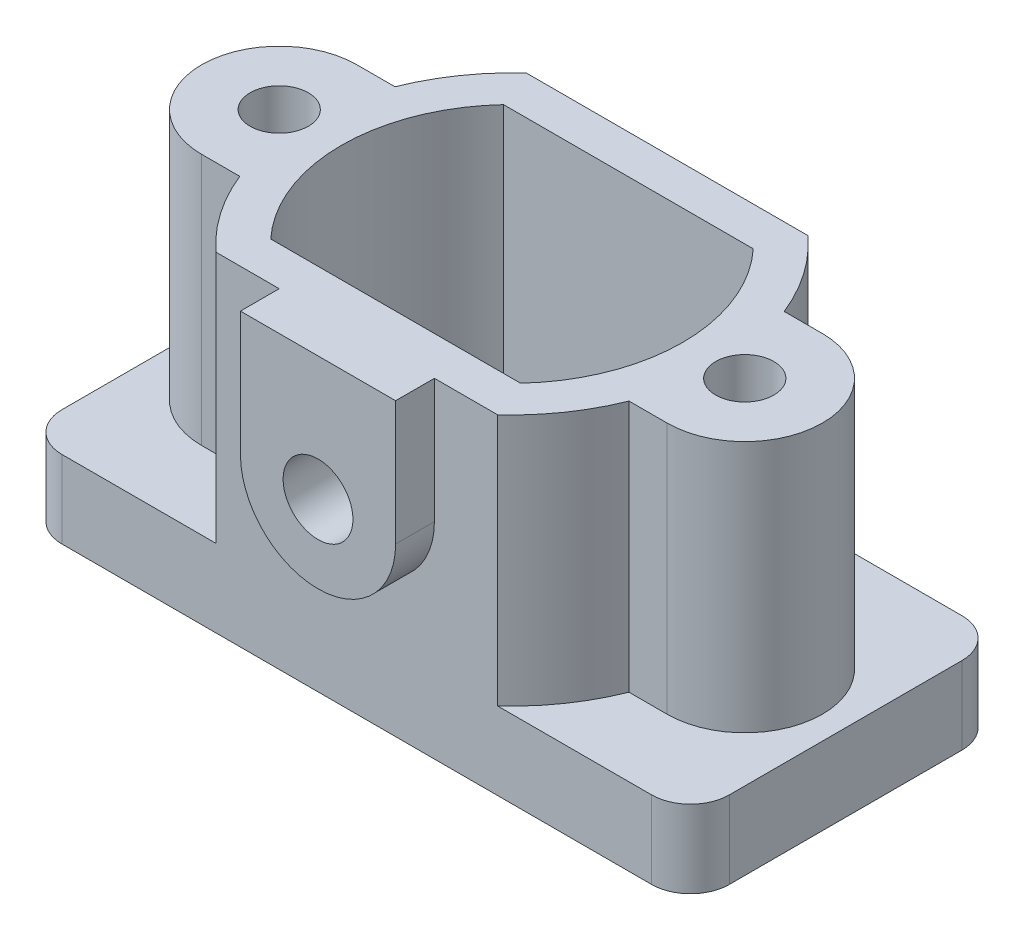
SolidWorks part; units mm, degrees
material "铜"
ref_plane "前视基准面" through (0, 0, 0) normal (0, 0, 1) x (1, 0, 0)
ref_plane "上视基准面" through (0, 0, 0) normal (0, 1, 0) x (1, 0, 0)
ref_plane "右视基准面" through (0, 0, 0) normal (1, 0, 0) x (0, 0, -1)
other "Configuration Table"
other "红铜"
sketch "草图1" plane through (0, 0, 0) normal (0, 1, 0) x (1, 0, 0)
  line L1 (-76, 40) -> (76, 40)
  line L2 (-86, 30) -> (-86, -30)
  line L3 (-76, -40) -> (76, -40)
  line L4 (86, 30) -> (86, -30)
  line L5 (-86, 40) -> (86, -40) construction
  line L6 (-86, -40) -> (86, 40) construction
  arc A0 (-86, -30) -> (-76, -40) centre (-76, -30) ccw
  arc A1 (76, -40) -> (86, -30) centre (76, -30) ccw
  arc A2 (76, 40) -> (86, 30) centre (76, 30) cw
  arc A3 (-76, 40) -> (-86, 30) centre (-76, 30) ccw
  point P0 (0, 0)
  dimension "D1" = 10
extrude "凸台-拉伸1" add sketch "草图1" along normal blind 20
sketch "草图2" plane through (0, 20, 0) normal (0, 1, 0) x (1, 0, 0)
  line L0 (-94.4477, 0) -> (99.6134, 0) construction
  line L1 (0, 84.2538) -> (0, -110.201) construction
  line L2 (33.813, 12.5) -> (33.813, -12.5)
  line L3 (33.813, 12.5) -> (18.7083, 12.5)
  line L4 (33.813, -12.5) -> (18.7083, -12.5)
  line L5 (-33.813, -12.5) -> (-18.7083, -12.5)
  line L6 (-33.813, 12.5) -> (-33.813, -12.5)
  line L7 (-33.813, 12.5) -> (-18.7083, 12.5)
  arc A0 (-18.7083, -12.5) -> (18.7083, -12.5) centre (0, 0) ccw
  arc A1 (18.7083, 12.5) -> (-18.7083, 12.5) centre (0, 0) ccw
  point P8 (33.813, 0)
  dimension "D1" = 45
extrude "切除-拉伸1" cut sketch "草图2" against normal through all both and the other way through all
sketch "草图3" plane through (0, 20, 0) normal (0, 1, 0) x (1, 0, 0)
  line L0 (60, 20) -> (50.1597, 20)
  line L1 (-101.9561, 0) -> (92.8964, 0) construction
  line L2 (-30, -30) -> (30, -30)
  line L3 (-76, -40) -> (76, -40) construction
  line L4 (76, 40) -> (-76, 40) construction
  line L5 (-36.2767, -40) -> (36.2767, -40)
  line L6 (36.2767, 40) -> (-36.2767, 40)
  line L7 (0, 40) -> (0, -40) construction
  line L8 (60, -20) -> (50.1597, -20)
  line L9 (-32.187, -30) -> (32.187, -30)
  line L10 (-60, -20) -> (-50.1597, -20)
  line L11 (-60, 20) -> (-50.1597, 20)
  line L13 (32.187, 30) -> (-32.187, 30)
  arc A0 (-36.2767, 40) -> (-50.1597, 20) centre (0, 0) ccw
  arc A1 (36.2767, -40) -> (50.1597, -20) centre (0, 0) ccw
  arc A2 (60, -20) -> (60, 20) centre (60, 0) ccw
  circle A3 centre (60, 0) radius 7.5
  arc A4 (53.8312, -4.2657) -> (53.8312, 4.2657) centre (0, 0) ccw
  arc A5 (-32.187, 30) -> (-32.187, -30) centre (0, 0) ccw
  arc A6 (32.187, -30) -> (32.187, 30) centre (0, 0) ccw
  arc A7 (-29.5588, 32.5926) -> (-29.5588, -32.5926) centre (0, 0) ccw construction
  arc A8 (29.5588, -32.5926) -> (29.5588, 32.5926) centre (0, 0) ccw construction
  arc A9 (36.2767, -40) -> (36.2767, 40) centre (0, 0) ccw construction
  arc A10 (50.1597, 20) -> (36.2767, 40) centre (0, 0) ccw
  arc A11 (-60, -20) -> (-60, 20) centre (-60, 0) cw
  circle A12 centre (-60, 0) radius 7.5
  arc A14 (-36.2767, 40) -> (-36.2767, -40) centre (0, 0) ccw construction
  arc A15 (-50.1597, -20) -> (-36.2767, -40) centre (0, 0) ccw
  point P8 (0, -30)
  point P9 (0, -30)
  line M32 (-76, -40) -> (76, -40)
  line M36 (76, 40) -> (-76, 40)
  dimension "D2" = 108
  dimension "D3" = 40
  dimension "D4" = 15
  dimension "D1" = 30
  dimension "D5" = 60
  dimension "D6" = 10
extrude "凸台-拉伸2" add sketch "草图3" along normal blind 65 contours L10 A15 A1 L8 A2 L0 A10 A0 L11 A11 A3 A6 L9 L2 A5 L13 A12 M32 M36
sketch "草图4" plane through (0, 85, 0) normal (0, 1, 0) x (1, 0, 0)
  line L6 (-60, -20) -> (-50.1597, -20)
  line L7 (-36.2767, -40) -> (36.2767, -40)
  line L8 (50.1597, -20) -> (60, -20)
  line L9 (60, 20) -> (50.1597, 20)
  line L10 (36.2767, 40) -> (-36.2767, 40)
  line L11 (-50.1597, 20) -> (-60, 20)
  line L12 (-60, -20) -> (-50.1597, -20)
  line L13 (-36.2767, -40) -> (36.2767, -40)
  line L14 (50.1597, -20) -> (60, -20)
  line L15 (60, 20) -> (50.1597, 20)
  line L16 (36.2767, 40) -> (-36.2767, 40)
  line L17 (-50.1597, 20) -> (-60, 20)
  arc A6 (-50.1597, -20) -> (-36.2767, -40) centre (0, 0) ccw
  arc A7 (36.2767, -40) -> (50.1597, -20) centre (0, 0) ccw
  arc A8 (60, -20) -> (60, 20) centre (60, 0) ccw
  arc A9 (50.1597, 20) -> (36.2767, 40) centre (0, 0) ccw
  arc A10 (-36.2767, 40) -> (-50.1597, 20) centre (0, 0) ccw
  arc A11 (-60, 20) -> (-60, -20) centre (-60, 0) ccw
  arc A12 (-50.1597, -20) -> (-36.2767, -40) centre (0, 0) ccw
  arc A13 (36.2767, -40) -> (50.1597, -20) centre (0, 0) ccw
  arc A14 (60, -20) -> (60, 20) centre (60, 0) ccw
  arc A15 (50.1597, 20) -> (36.2767, 40) centre (0, 0) ccw
  arc A16 (-36.2767, 40) -> (-50.1597, 20) centre (0, 0) ccw
  arc A17 (-60, 20) -> (-60, -20) centre (-60, 0) ccw
  dimension "D1" = 0
sketch "草图5" plane through (0, 85, 0) normal (0, 1, 0) x (1, 0, 0)
  circle A0 centre (60, 0) radius 7.5 construction
  circle A1 centre (60, 0) radius 7.5
  circle A2 centre (-60, 0) radius 7.5 construction
  circle A3 centre (-60, 0) radius 7.5
extrude "切除-拉伸2" cut sketch "草图5" against normal through all both and the other way through all contours A3 | A1
sketch "草图6" plane through (0, 0, 40) normal (0, 0, 1) x (1, 0, 0)
  line L0 (0, 85) -> (-20, 85)
  line L1 (-36.2767, 85) -> (36.2767, 85) construction
  line L2 (-20, 85) -> (-20, 53)
  line L3 (20, 53) -> (20, 85)
  line L4 (20, 85) -> (0, 85)
  arc A0 (-20, 53) -> (20, 53) centre (0, 53) ccw
  circle A1 centre (0, 53) radius 9
  dimension "D3" = 18
  dimension "D1" = 20
  dimension "D2" = 20
  dimension "D4" = 32
extrude "凸台-拉伸3" add sketch "草图6" along normal blind 10
sketch "草图7" plane through (0, 0, 50) normal (0, 0, 1) x (1, 0, 0)
  circle A0 centre (0, 53) radius 9 construction
  circle A1 centre (0, 53) radius 9
extrude "切除-拉伸3" cut sketch "草图7" against normal up to surface (20 mm away) and the other way through all up to face at (0, 52.5, 30)
